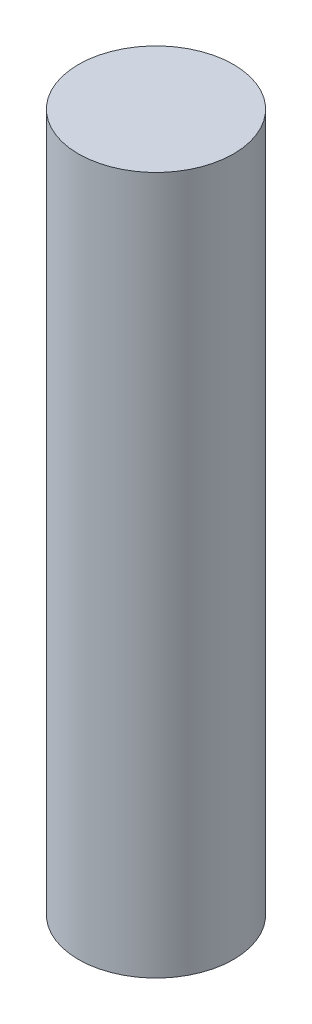
SolidWorks part; units mm, degrees
ref_plane "Front Plane" through (0, 0, 0) normal (0, 0, 1) x (1, 0, 0)
ref_plane "Top Plane" through (0, 0, 0) normal (0, 1, 0) x (1, 0, 0)
ref_plane "Right Plane" through (0, 0, 0) normal (1, 0, 0) x (0, 0, -1)
sketch "Sketch1" plane through (0, 0, 0) normal (0, 1, 0) x (1, 0, 0)
  circle A0 centre (0, 0) radius 15
  dimension "D1" = 30
sketch "Sketch2" plane through (0, 0, 0) normal (0, 1, 0) x (1, 0, 0)
  circle A0 centre (0, 0) radius 4
  dimension "D1" = 8
extrude "Boss-Extrude1" add sketch "Sketch2" along normal blind 36
sketch "Sketch3" plane through (0, 0, 0) normal (0, -1, 0) x (1, 0, 0)
  circle A0 centre (0, 0) radius 4
  dimension "D1" = 8
